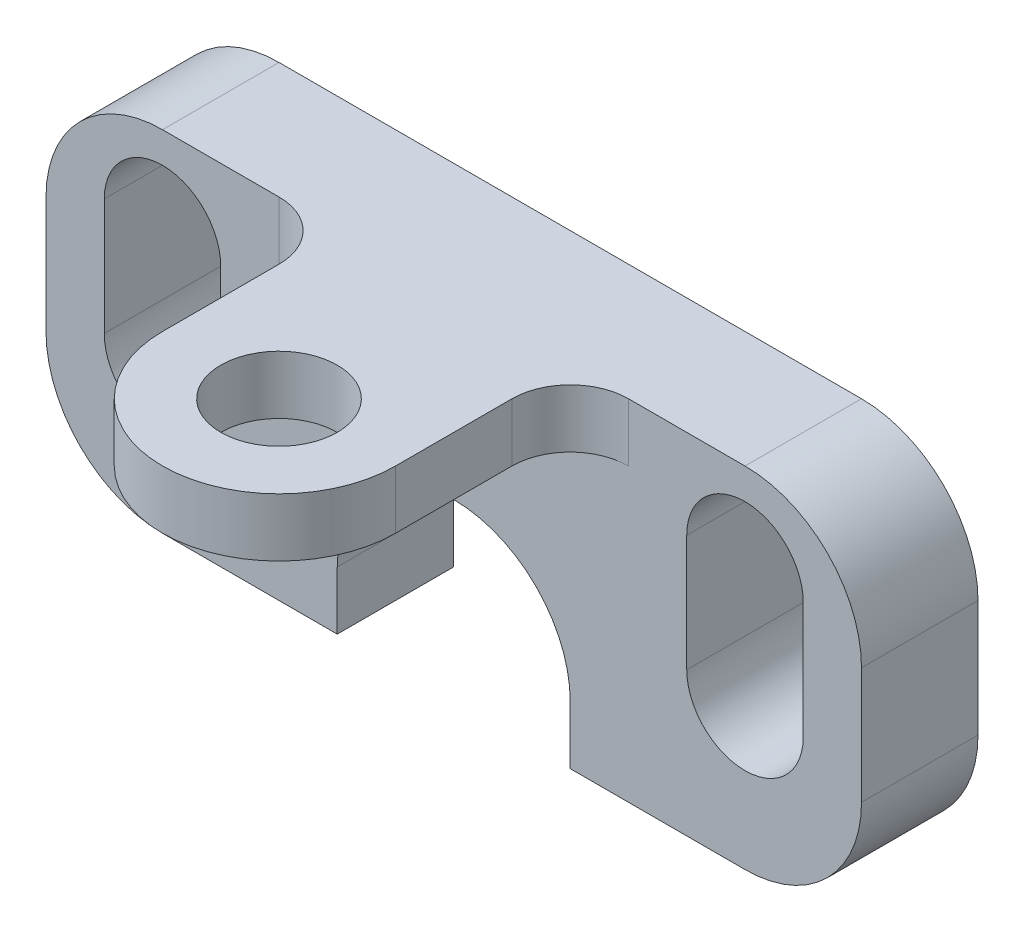
SolidWorks part; units mm, degrees
ref_plane "Front Plane" through (0, 0, 0) normal (0, 0, 1) x (1, 0, 0)
ref_plane "Top Plane" through (0, 0, 0) normal (0, 1, 0) x (1, 0, 0)
ref_plane "Right Plane" through (0, 0, 0) normal (1, 0, 0) x (0, 0, -1)
sketch "Sketch1" plane through (0, 0, 0) normal (0, 0, 1) x (1, 0, 0)
  line L0 (-10, -15) -> (-10, -10)
  line L1 (-25, -15) -> (-10, -15)
  line L2 (-35, -5) -> (-35, 5)
  line L3 (-25, 15) -> (25, 15)
  line L4 (35, -5) -> (35, 5)
  line L5 (10, -15) -> (10, -10)
  line L6 (10, -15) -> (25, -15)
  line L7 (25, 7.3542) -> (25, -2.6458) construction
  line L8 (30, 7.3542) -> (30, -2.6458)
  line L9 (20, 7.3542) -> (20, -2.6458)
  line L10 (-25, 7.3542) -> (-25, -2.6458) construction
  line L11 (-20, 7.3542) -> (-20, -2.6458)
  line L12 (-30, 7.3542) -> (-30, -2.6458)
  arc A0 (10, -10) -> (-10, -10) centre (0, -10) ccw
  arc A1 (30, 7.3542) -> (20, 7.3542) centre (25, 7.3542) ccw
  arc A2 (20, -2.6458) -> (30, -2.6458) centre (25, -2.6458) ccw
  arc A3 (-20, 7.3542) -> (-30, 7.3542) centre (-25, 7.3542) ccw
  arc A4 (-30, -2.6458) -> (-20, -2.6458) centre (-25, -2.6458) ccw
  arc A5 (25, -15) -> (35, -5) centre (25, -5) ccw
  arc A6 (35, 5) -> (25, 15) centre (25, 5) ccw
  arc A7 (-25, 15) -> (-35, 5) centre (-25, 5) ccw
  arc A8 (-25, -15) -> (-35, -5) centre (-25, -5) cw
  point P0 (0, 0)
  point P13 (25, 2.3542)
  point P18 (-25, 2.3542)
  point P25 (0, 0)
  point P30 (35, 15)
  point P33 (-35, 15)
  point P36 (-35, -15)
  dimension "D13" = 10
  dimension "D1" = 50
  dimension "D2" = 25
  dimension "D3" = 5
  dimension "D4" = 5
  dimension "D5" = 10
  dimension "D6" = 10
  dimension "D7" = 70
  dimension "D8" = 35
  dimension "D9" = 30
  dimension "D10" = 10
  dimension "D11" = 15
  dimension "D12" = 10
extrude "Boss-Extrude1" add sketch "Sketch1" along normal blind 10
sketch "Sketch2" plane through (0, 0, 10) normal (0, 0, 1) x (1, 0, 0)
  line L0 (25, 15) -> (-25, 15) construction
  line L1 (10, 15) -> (-10, 15)
  line L2 (10, 15) -> (10, 10)
  line L3 (10, 10) -> (-10, 10)
  line L4 (-10, 15) -> (-10, 10)
  dimension "D1" = 20
  dimension "D2" = 5
  dimension "D3" = 15
  dimension "D4" = 15
extrude "Boss-Extrude2" add sketch "Sketch2" along normal blind 15
fillet "Fillet3" radius 5 1 edges at (-10, 12.5, 10)
fillet "Fillet4" radius 5 1 edges at (10, 12.5, 10)
sketch "Sketch3" plane through (0, 15, 0) normal (0, 1, 0) x (1, 0, 0)
  line L0 (10, -25) -> (-10, -25) construction
  line L1 (-10, -25) -> (10, -25)
  arc A0 (-10, -25) -> (10, -25) centre (0, -25) ccw
extrude "Boss-Extrude4" add sketch "Sketch3" against normal blind 5
sketch "Sketch4" plane through (0, 15, 0) normal (0, 1, 0) x (1, 0, 0)
  circle A0 centre (0, -25) radius 5
extrude "Cut-Extrude1" cut sketch "Sketch4" against normal blind 5
